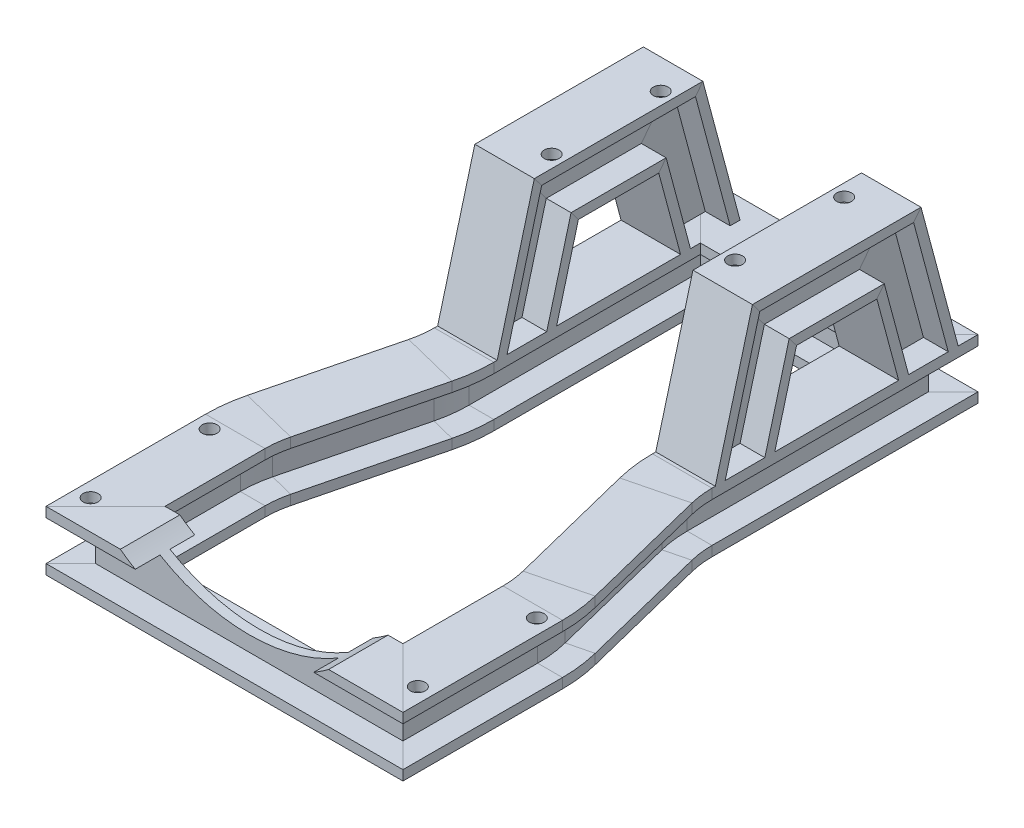
SolidWorks part; units mm, degrees
material "Plain Carbon Steel"
ref_plane "Front Plane" through (0, 0, 0) normal (0, 0, 1) x (1, 0, 0)
ref_plane "Top Plane" through (0, 0, 0) normal (0, 1, 0) x (1, 0, 0)
ref_plane "Right Plane" through (0, 0, 0) normal (1, 0, 0) x (0, 0, -1)
sketch "Sketch1" plane through (0, 0, 0) normal (0, 1, 0) x (1, 0, 0)
  line L0 (-28, 62) -> (28, 62)
  line L1 (28, 62) -> (28, 8.339)
  line L2 (28.5673, 3.7308) -> (35.0744, -22.2977)
  line L3 (36, -29.8163) -> (36, -62)
  line L4 (36, -62) -> (-36, -62)
  line L5 (-36, -62) -> (-36, -29.8163)
  line L6 (-35.0744, -22.2977) -> (-28.5673, 3.7308)
  line L7 (-28, 8.339) -> (-28, 62)
  arc A0 (28, 8.339) -> (28.5673, 3.7308) centre (47, 8.339) ccw
  arc A1 (-28.5673, 3.7308) -> (-28, 8.339) centre (-47, 8.339) ccw
  arc A2 (35.0744, -22.2977) -> (36, -29.8163) centre (5, -29.8163) cw
  arc A3 (-36, -29.8163) -> (-35.0744, -22.2977) centre (-5, -29.8163) cw
  point P8 (0, 62)
  point P10 (0, -62)
  point P13 (28, 6)
  point P16 (-28, 6)
  point P19 (36, -26)
  point P22 (-36, -26)
  dimension "D9" = 19
  dimension "D10" = 19
  dimension "D11" = 31
  dimension "D12" = 31
  dimension "D1" = 56
  dimension "D2" = 72
  dimension "D3" = 56
  dimension "D4" = 36
  dimension "D5" = 36
  dimension "D6" = 56
  dimension "D7" = 124
  dimension "D8" = 62
ref_plane "Plane1" through (0, 0, -62) normal (0, 0, 1) x (1, 0, 0)
sketch "Sketch2" plane through (0, 0, -62) normal (0, 0, 1) x (1, 0, 0)
  line L0 (28, 0) -> (16, 0)
  line L1 (16, 0) -> (16, 2)
  line L2 (16, 2) -> (21, 2)
  line L3 (21, 2) -> (21, 10)
  line L4 (21, 10) -> (16, 10)
  line L5 (16, 10) -> (16, 12)
  line L6 (16, 12) -> (28, 12)
  line L7 (28, 12) -> (28, 10)
  line L8 (28, 10) -> (23, 10)
  line L9 (23, 10) -> (23, 2)
  line L10 (23, 2) -> (28, 2)
  line L11 (28, 2) -> (28, 0)
  dimension "D1" = 12
  dimension "D2" = 12
  dimension "D3" = 12
  dimension "D4" = 2
  dimension "D5" = 2
  dimension "D6" = 2
  dimension "D7" = 2
  dimension "D8" = 5
sweep "Sweep1" add profiles "Sketch2" path "Sketch1"
sketch "Sketch3" plane through (28, 0, 0) normal (1, 0, 0) x (0, 0, -1)
  line L0 (9, 12) -> (16.5, 40)
  line L1 (62, 12) -> (8.339, 12) construction
  line L2 (16.5, 40) -> (50.5, 40)
  line L5 (-62, 10) -> (-62, 12) construction
  line L6 (50.5, 40) -> (58, 12)
  line L7 (62, 10) -> (62, 12) construction
  line L8 (9, 12) -> (58, 12) construction
  point P11 (33.5, 40)
  point P12 (33.5, 12)
  dimension "D1" = 71
  dimension "D2" = 34
  dimension "D3" = 4
  dimension "D4" = 28
sketch "Sketch4" plane through (0, 12, 0) normal (0, 1, 0) x (1, 0, 0)
  line L0 (28, 58) -> (16, 58)
  line L1 (28, 9) -> (28, 58) construction
  line L2 (16, 58) -> (16, 56)
  line L3 (16, 56) -> (21, 56)
  line L4 (21, 56) -> (21, 48)
  line L5 (21, 48) -> (16, 48)
  line L6 (16, 48) -> (16, 46)
  line L7 (16, 46) -> (28, 46)
  line L8 (28, 46) -> (28, 48)
  line L9 (28, 48) -> (23, 48)
  line L10 (23, 48) -> (23, 56)
  line L11 (23, 56) -> (28, 56)
  line L12 (28, 56) -> (28, 58)
  line L13 (-16, 50) -> (16, 50) construction
  dimension "D1" = 12
  dimension "D2" = 12
  dimension "D3" = 2
  dimension "D4" = 2
  dimension "D5" = 2
  dimension "D6" = 2
  dimension "D7" = 12
  dimension "D8" = 5
  dimension "D9" = 4
sweep "Sweep2" add profiles "Sketch4" path "Sketch3"
ref_plane "Plane2" through (22, 0, 0) normal (1, 0, 0) x (0, 0, -1)
sketch "Sketch5" plane through (22, 0, 0) normal (1, 0, 0) x (0, 0, -1)
  line L0 (17.6611, 7.0015) -> (18.4643, 10) construction
  line L1 (17.6611, 7.0015) -> (19.3933, 6.0018) construction
  line L2 (19.3933, 6.0018) -> (20.4643, 10) construction
  line L3 (17.6611, 7.0015) -> (18.4643, 10)
  line L4 (17.6611, 7.0015) -> (19.3933, 6.0018)
  line L5 (19.3933, 6.0018) -> (20.4643, 10)
  line L6 (18.4643, 10) -> (20.4643, 10)
extrude "Cut-Extrude1" cut sketch "Sketch5" against normal blind 5 from offset 1 offset against normal yes
mirror "Mirror1" about plane through (22, 0, 0) normal (1, 0, 0) of "Cut-Extrude1"
mirror "Mirror2" about plane through (0, 0, 0) normal (1, 0, 0) of "Mirror1", "Cut-Extrude1", "Sweep2"
sketch "Sketch6" plane through (0, 40, 0) normal (0, 1, 0) x (1, 0, 0)
  line L1 (-24, 58) -> (-28, 58) construction
  line L2 (0, 62) -> (0, 0) construction
  line L3 (-22, 62) -> (22, 62) construction
  circle A0 centre (18.5, 44.5) radius 1.5
  circle A1 centre (18.5, 22.5) radius 1.5
  circle A2 centre (-18.5, 44.5) radius 1.5
  circle A3 centre (-18.5, 22.5) radius 1.5
  dimension "D1" = 3
  dimension "D2" = 3
  dimension "D3" = 37
  dimension "D4" = 37
  dimension "D5" = 13.5
  dimension "D6" = 22
extrude "Cut-Extrude2" cut sketch "Sketch6" against normal up to next
sketch "Sketch7" plane through (0, 12, 0) normal (0, 1, 0) x (1, 0, 0)
  line L0 (0, 0) -> (0, -62) construction
  line L1 (36, -62) -> (-36, -62) construction
  circle A0 centre (33, -32) radius 1.5
  circle A1 centre (33, -56) radius 1.5
  circle A2 centre (-33, -56) radius 1.5
  circle A3 centre (-33, -32) radius 1.5
  dimension "D1" = 66
  dimension "D2" = 66
  dimension "D3" = 24
  dimension "D5" = 3
  dimension "D4" = 6
extrude "Cut-Extrude3" cut sketch "Sketch7" against normal up to next
sketch "Sketch8" plane through (0, 0, 62) normal (0, 0, 1) x (1, 0, 0)
  line L0 (-21, 12) -> (21, 12) construction
  line L1 (36, 12) -> (-36, 12) construction
  line L2 (-18, 10) -> (18, 10) construction
  line L3 (31, 10) -> (-31, 10) construction
  line L4 (0, -22) -> (0, 22) construction
  circle A0 centre (0, 40.25) radius 35.2003
  point P8 (0, 10)
  dimension "D1" = 3
  dimension "D2" = 3
  dimension "D3" = 36
extrude "Cut-Extrude4" cut sketch "Sketch8" against normal blind 12
